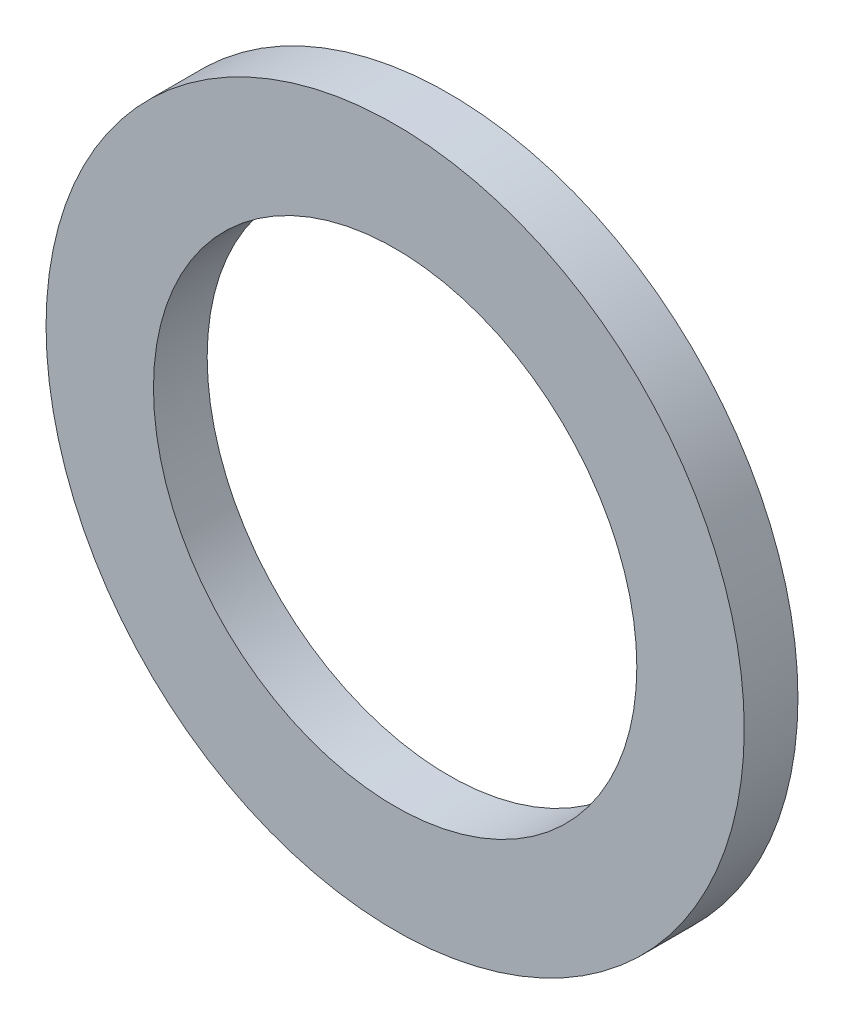
SolidWorks part; units mm, degrees
ref_plane "前视基准面" through (0, 0, 0) normal (0, 0, 1) x (1, 0, 0)
ref_plane "上视基准面" through (0, 0, 0) normal (0, 1, 0) x (1, 0, 0)
ref_plane "右视基准面" through (0, 0, 0) normal (1, 0, 0) x (0, 0, -1)
sketch "草图3" plane through (0, 0, 0) normal (0, 0, 1) x (1, 0, 0)
  circle A0 centre (0, 0) radius 9
  circle A1 centre (0, 0) radius 13
extrude "凸台-拉伸1" add sketch "草图3" along normal blind 2
